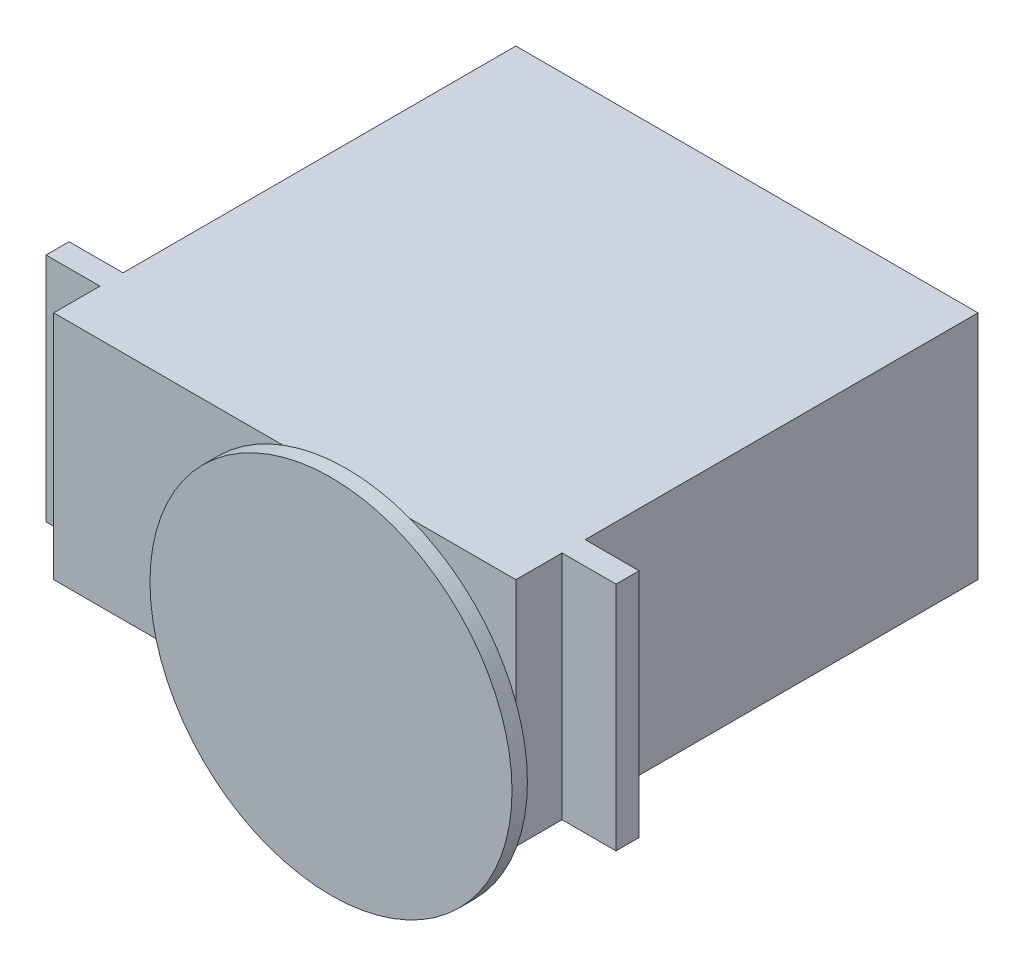
SolidWorks part; units mm, degrees
ref_plane "前视基准面" through (0, 0, 0) normal (0, 0, 1) x (1, 0, 0)
ref_plane "上视基准面" through (0, 0, 0) normal (0, 1, 0) x (1, 0, 0)
ref_plane "右视基准面" through (0, 0, 0) normal (1, 0, 0) x (0, 0, -1)
sketch "草图1" plane through (0, 0, 0) normal (0, 1, 0) x (1, 0, 0)
  line L1 (-30, 30) -> (30, 30)
  line L2 (-30, 30) -> (-30, -30)
  line L3 (-30, -30) -> (30, -30)
  line L4 (30, 30) -> (30, -30)
  line L5 (-30, 30) -> (30, -30) construction
  line L6 (-30, -30) -> (30, 30) construction
  point P0 (0, 0)
  dimension "D1" = 60
  dimension "D2" = 60
extrude "凸台-拉伸2" add sketch "草图1" along normal blind 30
sketch "草图3" plane through (0, 0, 30) normal (0, 0, 1) x (1, 0, 0)
  line L0 (-30, 30) -> (30, 30) construction
  line L1 (30, 30) -> (30, 0) construction
  circle A0 centre (15, 15) radius 3.5
  dimension "D1" = 7
  dimension "D3" = 15
  dimension "D2" = 15
extrude "凸台-拉伸3" add sketch "草图3" along normal blind 7
sketch "草图4" plane through (0, 0, 37) normal (0, 0, 1) x (1, 0, 0)
  circle A0 centre (15, 15) radius 23.5
  dimension "D1" = 47
extrude "凸台-拉伸4" add sketch "草图4" along normal blind 2
sketch "草图5" plane through (30, 0, 0) normal (1, 0, 0) x (0, 0, -1)
  line L0 (-30, 30) -> (30, 30) construction
  line L1 (-24, 30) -> (-21, 30)
  line L2 (-24, 30) -> (-24, 0)
  line L3 (-24, 0) -> (-21, 0)
  line L4 (-21, 30) -> (-21, 0)
  line L5 (-30, 0) -> (30, 0) construction
  line L6 (-30, 30) -> (-30, 0) construction
  dimension "D1" = 6
  dimension "D2" = 3
extrude "凸台-拉伸5" add sketch "草图5" along normal blind 7 and the other way blind 67
